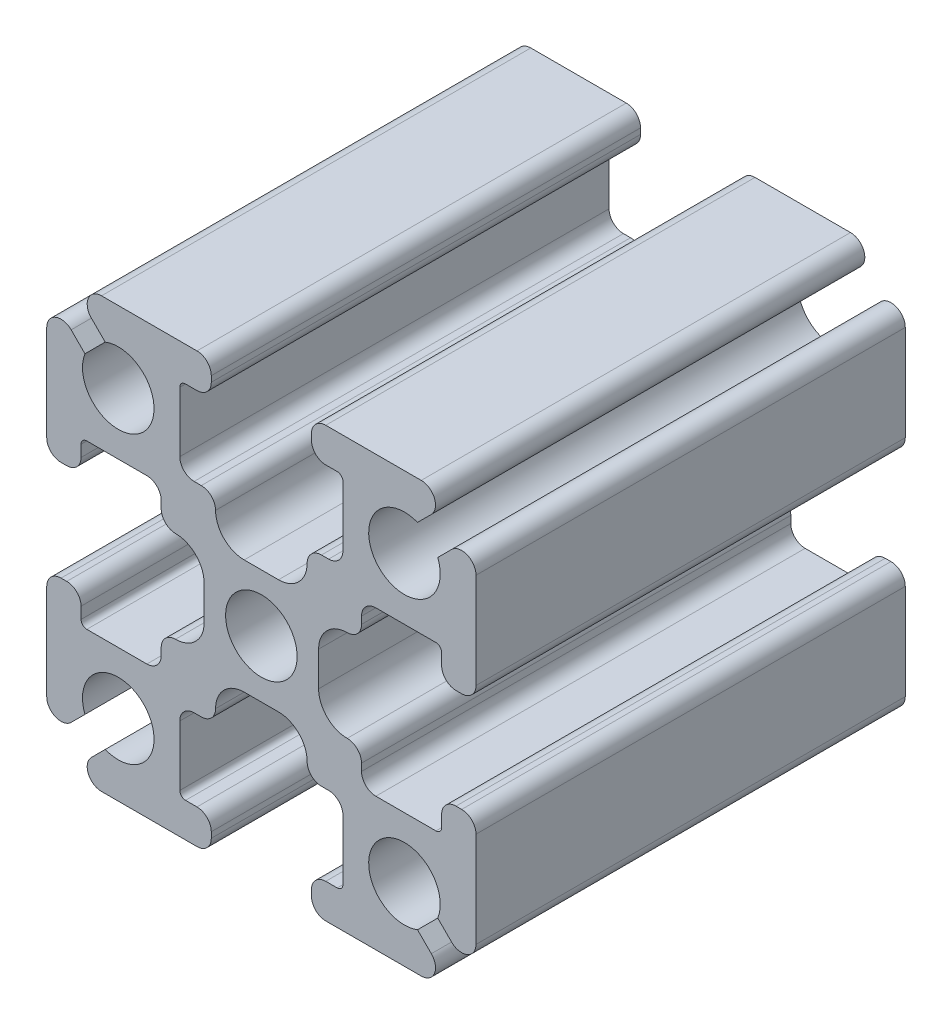
SolidWorks part; units mm, degrees
material "6063-T5"
ref_plane "Front Plane" through (0, 0, 0) normal (0, 0, 1) x (1, 0, 0)
ref_plane "Top Plane" through (0, 0, 0) normal (0, 1, 0) x (1, 0, 0)
ref_plane "Right Plane" through (0, 0, 0) normal (1, 0, 0) x (0, 0, -1)
sketch "Sketch1" plane through (0, 0, 0) normal (0, 0, 1) x (1, 0, 0)
  line L0 (6.6464, 5.9393) -> (6.1636, 5.4565)
  line L1 (5.4565, 6.1636) -> (5.9393, 6.6464)
  line L2 (5.5858, 7.5) -> (2.25, 7.5)
  line L3 (1.75, 7) -> (1.75, 6.8)
  line L4 (2.25, 6.3) -> (2.65, 6.3)
  line L5 (2.85, 6.1) -> (2.85, 4)
  line L6 (2.35, 3.5) -> (2.1, 3.5)
  line L7 (0.6, 2) -> (-0.6, 2)
  line L8 (-2.1, 3.5) -> (-2.35, 3.5)
  line L9 (-2.85, 4) -> (-2.85, 6.1)
  line L10 (-2.65, 6.3) -> (-2.25, 6.3)
  line L11 (-1.75, 6.8) -> (-1.75, 7)
  line L12 (-2.25, 7.5) -> (-5.5858, 7.5)
  line L13 (-5.9393, 6.6464) -> (-5.4565, 6.1636)
  line L14 (-6.1636, 5.4565) -> (-6.6464, 5.9393)
  line L15 (-7.5, 5.5858) -> (-7.5, 2.25)
  line L16 (-7, 1.75) -> (-6.8, 1.75)
  line L17 (-6.3, 2.25) -> (-6.3, 2.65)
  line L18 (-6.1, 2.85) -> (-4, 2.85)
  line L19 (-3.5, 2.35) -> (-3.5, 2.1)
  line L20 (-2, 0.6) -> (-2, -0.6)
  line L21 (-3.5, -2.1) -> (-3.5, -2.35)
  line L22 (-4, -2.85) -> (-6.1, -2.85)
  line L23 (-6.3, -2.65) -> (-6.3, -2.25)
  line L24 (-6.8, -1.75) -> (-7, -1.75)
  line L25 (-7.5, -2.25) -> (-7.5, -5.5858)
  line L26 (-6.6464, -5.9393) -> (-6.1636, -5.4565)
  line L27 (-5.4565, -6.1636) -> (-5.9393, -6.6464)
  line L28 (-5.5858, -7.5) -> (-2.25, -7.5)
  line L29 (-1.75, -7) -> (-1.75, -6.8)
  line L30 (-2.25, -6.3) -> (-2.65, -6.3)
  line L31 (-2.85, -6.1) -> (-2.85, -4)
  line L32 (-2.35, -3.5) -> (-2.1, -3.5)
  line L33 (-0.6, -2) -> (0.6, -2)
  line L34 (2.1, -3.5) -> (2.35, -3.5)
  line L35 (2.85, -4) -> (2.85, -6.1)
  line L36 (2.65, -6.3) -> (2.25, -6.3)
  line L37 (1.75, -6.8) -> (1.75, -7)
  line L38 (2.25, -7.5) -> (5.5858, -7.5)
  line L39 (5.9393, -6.6464) -> (5.4565, -6.1636)
  line L40 (6.1636, -5.4565) -> (6.6464, -5.9393)
  line L41 (7.5, -5.5858) -> (7.5, -2.25)
  line L42 (7, -1.75) -> (6.8, -1.75)
  line L43 (6.3, -2.25) -> (6.3, -2.65)
  line L44 (6.1, -2.85) -> (4, -2.85)
  line L45 (3.5, -2.35) -> (3.5, -2.1)
  line L46 (2, -0.6) -> (2, 0.6)
  line L47 (3.5, 2.1) -> (3.5, 2.35)
  line L48 (4, 2.85) -> (6.1, 2.85)
  line L49 (6.3, 2.65) -> (6.3, 2.25)
  line L50 (6.8, 1.75) -> (7, 1.75)
  line L51 (7.5, 2.25) -> (7.5, 5.5858)
  circle A0 centre (0, 0) radius 1.25
  arc A1 (6.1636, 5.4565) -> (5.4565, 6.1636) centre (5, 5) cw
  arc A2 (5.9393, 6.6464) -> (5.5858, 7.5) centre (5.5858, 7) ccw
  arc A3 (2.25, 7.5) -> (1.75, 7) centre (2.25, 7) ccw
  arc A4 (1.75, 6.8) -> (2.25, 6.3) centre (2.25, 6.8) ccw
  arc A5 (2.65, 6.3) -> (2.85, 6.1) centre (2.65, 6.1) cw
  arc A6 (2.85, 4) -> (2.35, 3.5) centre (2.35, 4) cw
  arc A7 (2.1, 3.5) -> (1.6, 3) centre (2.1, 3) ccw
  arc A8 (1.6, 3) -> (0.6, 2) centre (0.6, 3) cw
  arc A9 (-0.6, 2) -> (-1.6, 3) centre (-0.6, 3) cw
  arc A10 (-1.6, 3) -> (-2.1, 3.5) centre (-2.1, 3) ccw
  arc A11 (-2.35, 3.5) -> (-2.85, 4) centre (-2.35, 4) cw
  arc A12 (-2.85, 6.1) -> (-2.65, 6.3) centre (-2.65, 6.1) cw
  arc A13 (-2.25, 6.3) -> (-1.75, 6.8) centre (-2.25, 6.8) ccw
  arc A14 (-1.75, 7) -> (-2.25, 7.5) centre (-2.25, 7) ccw
  arc A15 (-5.5858, 7.5) -> (-5.9393, 6.6464) centre (-5.5858, 7) ccw
  arc A16 (-5.4565, 6.1636) -> (-6.1636, 5.4565) centre (-5, 5) cw
  arc A17 (-6.6464, 5.9393) -> (-7.5, 5.5858) centre (-7, 5.5858) ccw
  arc A18 (-7.5, 2.25) -> (-7, 1.75) centre (-7, 2.25) ccw
  arc A19 (-6.8, 1.75) -> (-6.3, 2.25) centre (-6.8, 2.25) ccw
  arc A20 (-6.3, 2.65) -> (-6.1, 2.85) centre (-6.1, 2.65) cw
  arc A21 (-4, 2.85) -> (-3.5, 2.35) centre (-4, 2.35) cw
  arc A22 (-3.5, 2.1) -> (-3, 1.6) centre (-3, 2.1) ccw
  arc A23 (-3, 1.6) -> (-2, 0.6) centre (-3, 0.6) cw
  arc A24 (-2, -0.6) -> (-3, -1.6) centre (-3, -0.6) cw
  arc A25 (-3, -1.6) -> (-3.5, -2.1) centre (-3, -2.1) ccw
  arc A26 (-3.5, -2.35) -> (-4, -2.85) centre (-4, -2.35) cw
  arc A27 (-6.1, -2.85) -> (-6.3, -2.65) centre (-6.1, -2.65) cw
  arc A28 (-6.3, -2.25) -> (-6.8, -1.75) centre (-6.8, -2.25) ccw
  arc A29 (-7, -1.75) -> (-7.5, -2.25) centre (-7, -2.25) ccw
  arc A30 (-7.5, -5.5858) -> (-6.6464, -5.9393) centre (-7, -5.5858) ccw
  arc A31 (-6.1636, -5.4565) -> (-5.4565, -6.1636) centre (-5, -5) cw
  arc A32 (-5.9393, -6.6464) -> (-5.5858, -7.5) centre (-5.5858, -7) ccw
  arc A33 (-2.25, -7.5) -> (-1.75, -7) centre (-2.25, -7) ccw
  arc A34 (-1.75, -6.8) -> (-2.25, -6.3) centre (-2.25, -6.8) ccw
  arc A35 (-2.65, -6.3) -> (-2.85, -6.1) centre (-2.65, -6.1) cw
  arc A36 (-2.85, -4) -> (-2.35, -3.5) centre (-2.35, -4) cw
  arc A37 (-2.1, -3.5) -> (-1.6, -3) centre (-2.1, -3) ccw
  arc A38 (-1.6, -3) -> (-0.6, -2) centre (-0.6, -3) cw
  arc A39 (0.6, -2) -> (1.6, -3) centre (0.6, -3) cw
  arc A40 (1.6, -3) -> (2.1, -3.5) centre (2.1, -3) ccw
  arc A41 (2.35, -3.5) -> (2.85, -4) centre (2.35, -4) cw
  arc A42 (2.85, -6.1) -> (2.65, -6.3) centre (2.65, -6.1) cw
  arc A43 (2.25, -6.3) -> (1.75, -6.8) centre (2.25, -6.8) ccw
  arc A44 (1.75, -7) -> (2.25, -7.5) centre (2.25, -7) ccw
  arc A45 (5.5858, -7.5) -> (5.9393, -6.6464) centre (5.5858, -7) ccw
  arc A46 (5.4565, -6.1636) -> (6.1636, -5.4565) centre (5, -5) cw
  arc A47 (6.6464, -5.9393) -> (7.5, -5.5858) centre (7, -5.5858) ccw
  arc A48 (7.5, -2.25) -> (7, -1.75) centre (7, -2.25) ccw
  arc A49 (6.8, -1.75) -> (6.3, -2.25) centre (6.8, -2.25) ccw
  arc A50 (6.3, -2.65) -> (6.1, -2.85) centre (6.1, -2.65) cw
  arc A51 (4, -2.85) -> (3.5, -2.35) centre (4, -2.35) cw
  arc A52 (3.5, -2.1) -> (3, -1.6) centre (3, -2.1) ccw
  arc A53 (3, -1.6) -> (2, -0.6) centre (3, -0.6) cw
  arc A54 (2, 0.6) -> (3, 1.6) centre (3, 0.6) cw
  arc A55 (3, 1.6) -> (3.5, 2.1) centre (3, 2.1) ccw
  arc A56 (3.5, 2.35) -> (4, 2.85) centre (4, 2.35) cw
  arc A57 (6.1, 2.85) -> (6.3, 2.65) centre (6.1, 2.65) cw
  arc A58 (6.3, 2.25) -> (6.8, 1.75) centre (6.8, 2.25) ccw
  arc A59 (7, 1.75) -> (7.5, 2.25) centre (7, 2.25) ccw
  arc A60 (7.5, 5.5858) -> (6.6464, 5.9393) centre (7, 5.5858) ccw
extrude "Boss-Extrude1" add sketch "Sketch1" along normal blind 15
